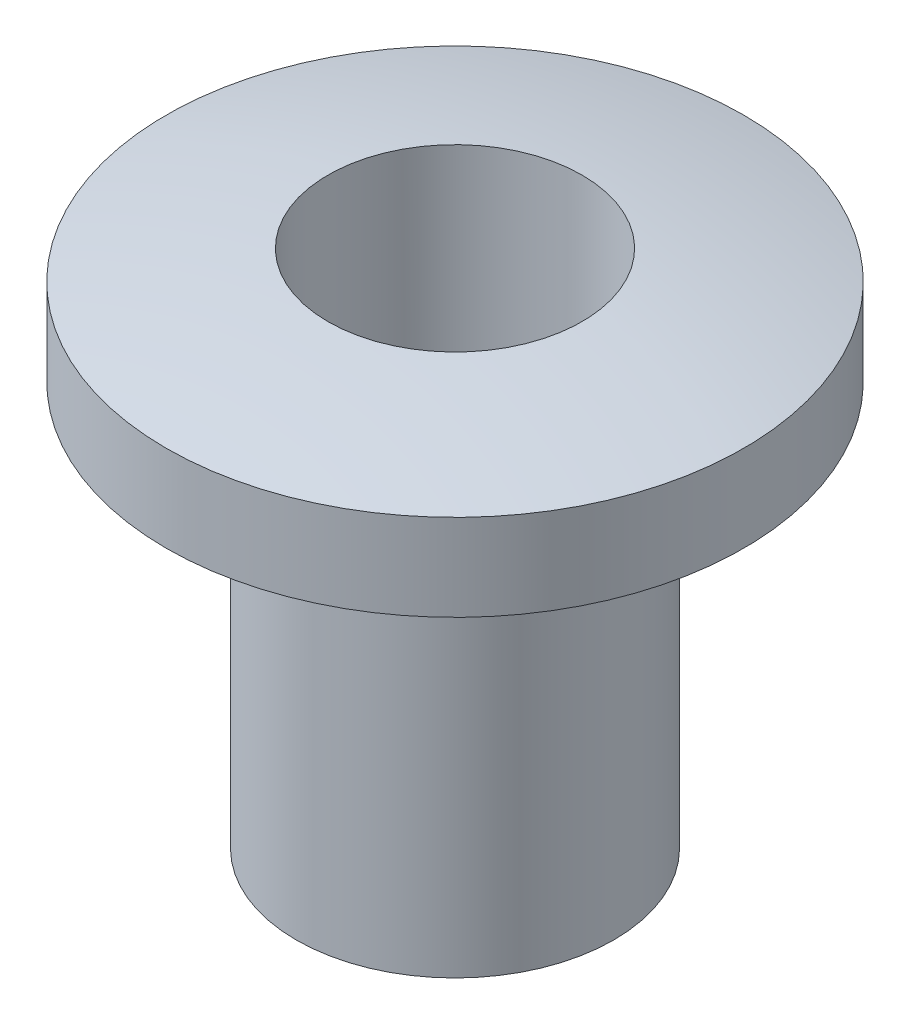
SolidWorks part; units mm, degrees
ref_plane "Front" through (0, 0, 0) normal (0, 0, 1) x (1, 0, 0)
ref_plane "Top" through (0, 0, 0) normal (0, 1, 0) x (1, 0, 0)
ref_plane "Right" through (0, 0, 0) normal (1, 0, 0) x (0, 0, -1)
sketch "Sketch1" plane through (0, 0, 0) normal (1, 0, 0) x (0, 0, -1)
  line L0 (0, 14.1505) -> (0, 0) construction
  line L1 (0, 0) -> (15.5054, 0) construction
  line L2 (2.2, 0) -> (2.2, 9)
  line L4 (5, 8.5) -> (5, 7)
  line L5 (5, 7) -> (2.75, 7)
  line L6 (2.75, 7) -> (2.75, 0)
  line L7 (2.75, 0) -> (2.2, 0)
  arc A0 (5, 8.5) -> (2.2, 9) centre (0, -11.41) ccw
  dimension "D1" = 7
  dimension "D2" = 4.4
  dimension "D3" = 5.5
  dimension "D4" = 1.5
  dimension "D5" = 10
  dimension "D6" = 0.5
revolve "Revolve1" add sketch "Sketch1" angle 360 about L0
